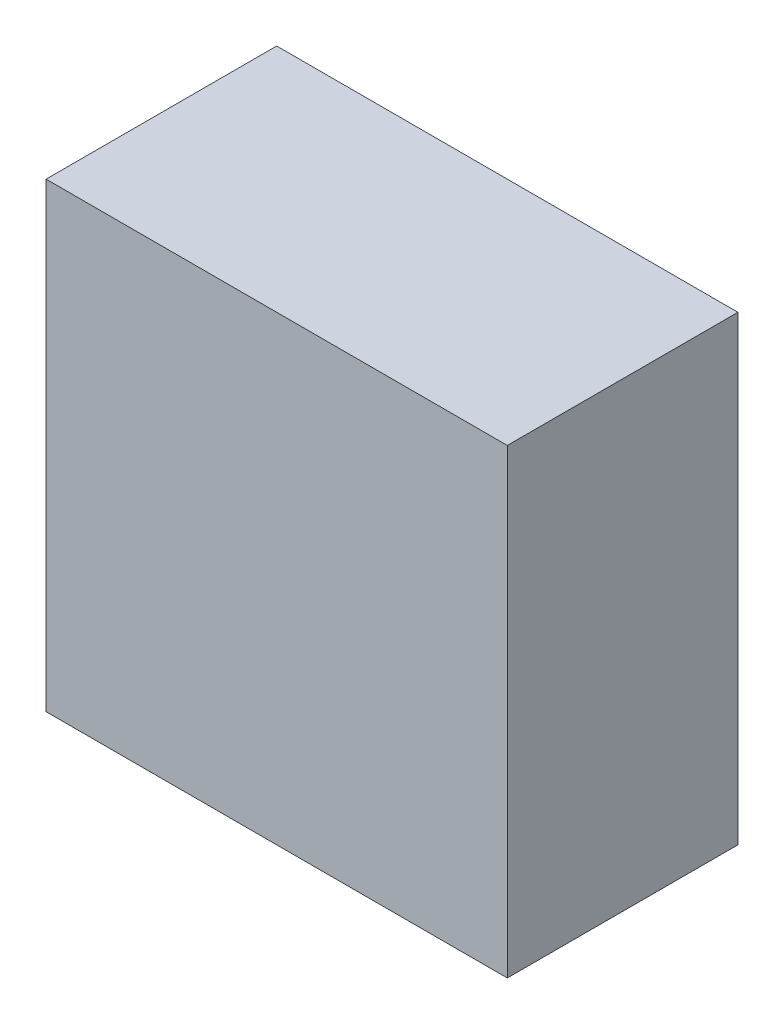
SolidWorks part; units mm, degrees
ref_plane "前视基准面" through (0, 0, 0) normal (0, 0, 1) x (1, 0, 0)
ref_plane "上视基准面" through (0, 0, 0) normal (0, 1, 0) x (1, 0, 0)
ref_plane "右视基准面" through (0, 0, 0) normal (1, 0, 0) x (0, 0, -1)
sketch "草图1" plane through (0, 0, 0) normal (0, 1, 0) x (1, 0, 0)
  line L1 (-20, 10) -> (20, 10)
  line L2 (-20, 10) -> (-20, -10)
  line L3 (-20, -10) -> (20, -10)
  line L4 (20, 10) -> (20, -10)
  line L5 (-20, 10) -> (20, -10) construction
  line L6 (-20, -10) -> (20, 10) construction
  point P0 (0, 0)
  dimension "D1" = 20
  dimension "D2" = 40
extrude "凸台-拉伸1" add sketch "草图1" along normal blind 40
